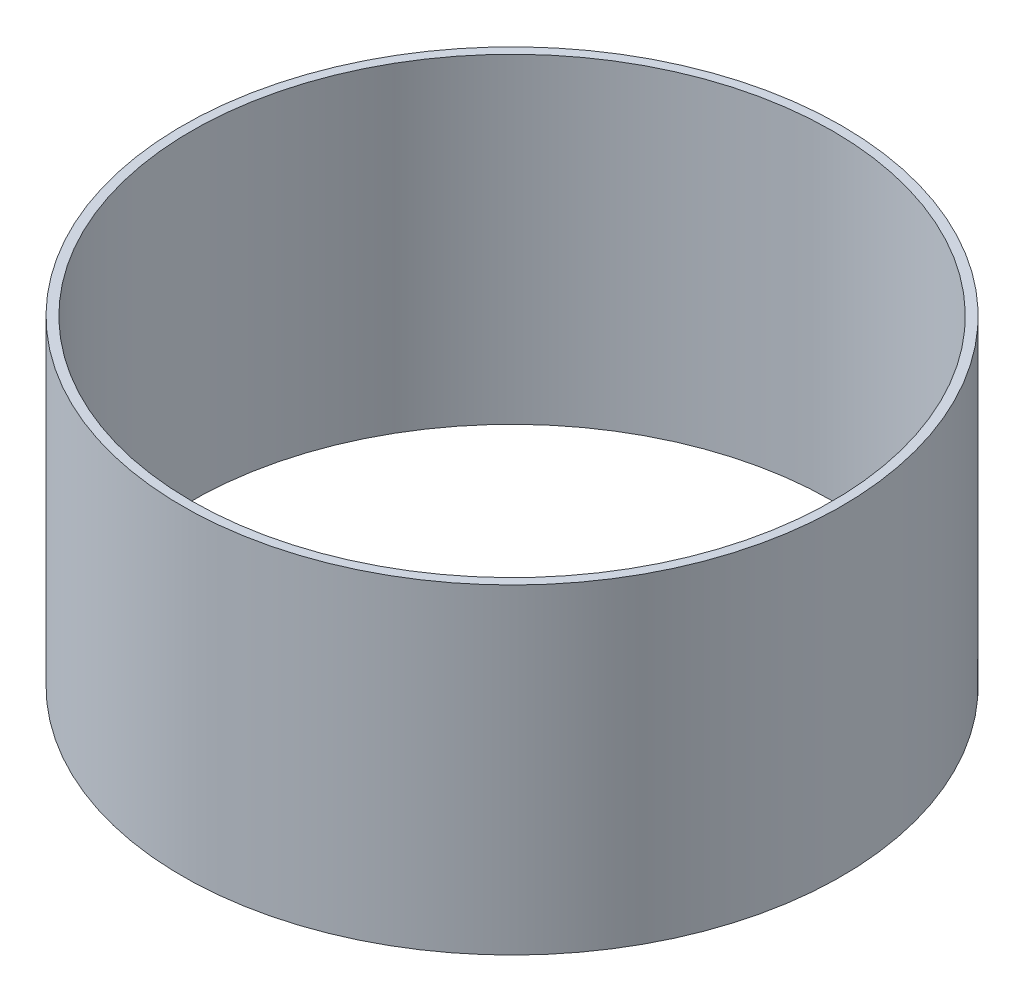
SolidWorks part; units mm, degrees
ref_plane "Front Plane" through (0, 0, 0) normal (0, 0, 1) x (1, 0, 0)
ref_plane "Top Plane" through (0, 0, 0) normal (0, 1, 0) x (1, 0, 0)
ref_plane "Right Plane" through (0, 0, 0) normal (1, 0, 0) x (0, 0, -1)
sketch "Sketch1" plane through (0, 0, 0) normal (0, 1, 0) x (1, 0, 0)
  circle A0 centre (0, 0) radius 76.2
  circle A1 centre (0, 0) radius 78.359
  dimension "D1" = 156.718
  dimension "D2" = 152.4
extrude "Boss-Extrude1" add sketch "Sketch1" along normal blind 76.2
